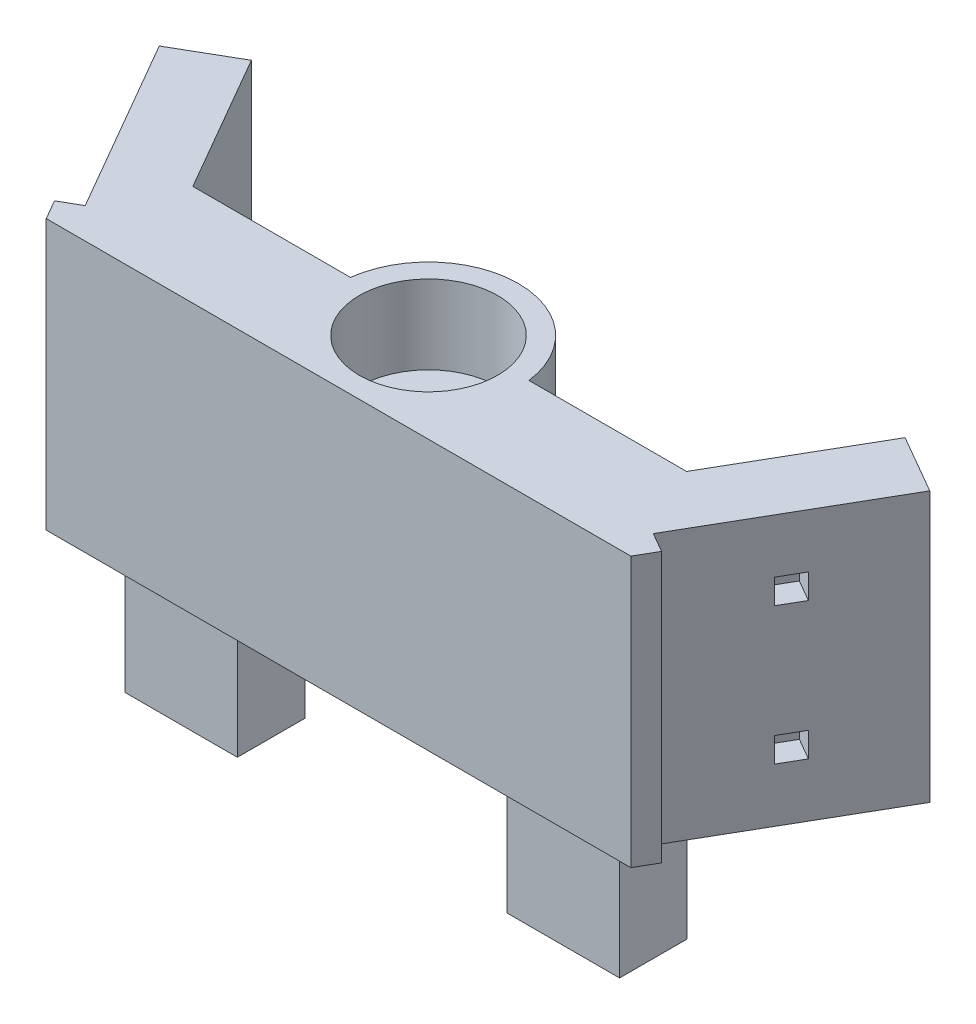
SolidWorks part; units mm, degrees
material "ABS"
ref_plane "Front Plane" through (0, 0, 0) normal (0, 0, 1) x (1, 0, 0)
ref_plane "Top Plane" through (0, 0, 0) normal (0, 1, 0) x (1, 0, 0)
ref_plane "Right Plane" through (0, 0, 0) normal (1, 0, 0) x (0, 0, -1)
sketch "Sketch1" plane through (0, 0, 0) normal (0, 1, 0) x (1, 0, 0)
  line L0 (-13, -4) -> (13, -4)
  line L1 (13, -4) -> (13.5, -3.134)
  line L2 (0, -2.5) -> (13.866, -2.5) construction
  line L3 (0, 0) -> (0, -4) construction
  line L6 (13.5, -3.134) -> (12.634, -2.634)
  line L7 (12.634, -2.634) -> (17.134, 5.1603)
  line L8 (17.134, 5.1603) -> (14.5359, 6.6603)
  line L9 (14.5359, 6.6603) -> (10.9793, 0.5)
  line L10 (-13, -4) -> (-13.5, -3.134)
  line L13 (-13.5, -3.134) -> (-12.634, -2.634)
  line L14 (-12.634, -2.634) -> (-17.134, 5.1603)
  line L15 (-17.134, 5.1603) -> (-14.5359, 6.6603)
  line L16 (-14.5359, 6.6603) -> (-10.9793, 0.5)
  line L17 (-11, 0.5) -> (-11, -2.5) construction
  line L18 (6, 0.5) -> (11, 0.5) construction
  line L19 (6, 0.5) -> (6, -2.5) construction
  line L20 (6, -2.5) -> (11, -2.5) construction
  line L21 (11, 0.5) -> (11, -2.5) construction
  line L22 (3.9686, 0.5) -> (10.9793, 0.5)
  line L23 (-10.9793, 0.5) -> (-3.9686, 0.5)
  line L24 (-6, -2.5) -> (-11, -2.5) construction
  line L25 (-6, 0.5) -> (-6, -2.5) construction
  line L26 (-6, 0.5) -> (-11, 0.5) construction
  circle A0 centre (0, 0) radius 2.5 construction
  arc A1 (-3.9686, 0.5) -> (3.9686, 0.5) centre (0, 0) cw
  dimension "D3" = 5
  dimension "D5" = 1.5
  dimension "D1" = 26
  dimension "D2" = 60
  dimension "D4" = 1.5
  dimension "D6" = 12
  dimension "D7" = 1
  dimension "D8" = 10
  dimension "D9" = 9
  dimension "D10" = 3
  dimension "D11" = 3
  dimension "D12" = 4.5
  dimension "D13" = 5
extrude "Boss-Extrude1" add sketch "Sketch1" along normal blind 12
hole_wizard "Ø2.5 (2.5) Diameter Hole1" positions "Sketch3" profile "Sketch2" hole size "Ø2.5" standard "ISO"
sketch "Sketch3" plane through (0, 12, 0) normal (0, 1, 0) x (1, 0, 0)
  point P0 (0, 0)
sketch "Sketch2" plane through (0, 12, 0) normal (1, 0, 0) x (0, 0, 1)
  line L0 (0, 0) -> (0, 10.7511)
  line L1 (0, 10.7511) -> (1.25, 10)
  line L2 (1.25, 10) -> (1.25, 0)
  line L5 (1.25, 0) -> (0, 0)
  line L10 (0, 10.7511) -> (-1.25, 10) construction
  line L11 (0, -6.35) -> (0, 107.95) construction
  dimension "Hole Dia." = 2.5
  dimension "Hole Depth" = 10
  dimension "Drill Angle" = 118
sketch "Sketch4" plane through (0, 12, 0) normal (0, 1, 0) x (1, 0, 0)
  circle A0 centre (0, 0) radius 3.0762
  dimension "D1" = 6.1524
extrude "Cut-Extrude1" cut sketch "Sketch4" against normal blind 3.5
sketch "Sketch5" plane through (0, 0, 0) normal (0, -1, 0) x (1, 0, 0)
  line L1 (6, 2.5) -> (11, 2.5)
  line L2 (6, 2.5) -> (6, -0.5)
  line L3 (6, -0.5) -> (11, -0.5)
  line L4 (11, 2.5) -> (11, -0.5)
  line L5 (-11, 2.5) -> (-6, 2.5)
  line L6 (-11, 2.5) -> (-11, -0.5)
  line L7 (-11, -0.5) -> (-6, -0.5)
  line L8 (-6, 2.5) -> (-6, -0.5)
extrude "Boss-Extrude2" add sketch "Sketch5" along normal blind 6
sketch "Sketch6" plane through (0, -6, 0) normal (0, -1, 0) x (1, 0, 0)
  line L0 (6, 2.5) -> (6, -0.5) construction
  line L1 (8, 1) -> (-8, 1)
  line L2 (8, 1) -> (8, -1)
  line L3 (8, -1) -> (-8, -1)
  line L4 (-8, 1) -> (-8, -1)
  line L5 (11, 2.5) -> (6, 2.5) construction
  line L6 (8, -1) -> (-8, 1) construction
  dimension "D1" = 2
  dimension "D2" = 1.5
extrude "Cut-Extrude2" [suppressed] cut sketch "Sketch6" against normal blind 14
sketch "Sketch7" plane through (-10.616, 0, 6.1292) normal (-0.866, 0, 0.5) x (0.5, 0, 0.866)
  line L0 (-8.5359, 8.5) -> (-8.5359, 3.5) construction
  line L1 (-9.0859, 9.6) -> (-7.9859, 9.6)
  line L2 (-9.0859, 9.6) -> (-9.0859, 8.5)
  line L3 (-9.0859, 8.5) -> (-7.9859, 8.5)
  line L4 (-7.9859, 9.6) -> (-7.9859, 8.5)
  line L5 (-8.5359, 6) -> (-4.0359, 6) construction
  line L6 (-4.0359, 12) -> (-4.0359, 0) construction
  line L9 (-9.0859, 3.5) -> (-7.9859, 3.5)
  line L10 (-9.0859, 3.5) -> (-9.0859, 2.4)
  line L11 (-9.0859, 2.4) -> (-7.9859, 2.4)
  line L12 (-7.9859, 3.5) -> (-7.9859, 2.4)
  line L14 (-13.0359, 12) -> (-13.0359, 0) construction
  line L15 (-8.5359, 6) -> (-13.0359, 6) construction
  dimension "D1" = 1.1
  dimension "D3" = 5
extrude "Cut-Extrude3" cut sketch "Sketch7" against normal blind 1.1
sketch "Sketch8" plane through (10.616, 0, 6.1292) normal (0.866, 0, 0.5) x (0.5, 0, -0.866)
  line L0 (8.5359, 8.5) -> (8.5359, 3.5) construction
  line L1 (8.5359, 6) -> (13.0359, 6) construction
  line L2 (13.0359, 12) -> (13.0359, 0) construction
  line L3 (8.5359, 6) -> (4.0359, 6) construction
  line L4 (4.0359, 12) -> (4.0359, 0) construction
  line L6 (7.9859, 9.6) -> (9.0859, 9.6)
  line L7 (7.9859, 9.6) -> (7.9859, 8.5)
  line L8 (7.9859, 8.5) -> (9.0859, 8.5)
  line L9 (9.0859, 9.6) -> (9.0859, 8.5)
  line L10 (7.9859, 2.4) -> (9.0859, 2.4)
  line L11 (7.9859, 2.4) -> (7.9859, 3.5)
  line L12 (7.9859, 3.5) -> (9.0859, 3.5)
  line L13 (9.0859, 2.4) -> (9.0859, 3.5)
  dimension "D1" = 1.1
  dimension "D2" = 5
extrude "Cut-Extrude4" cut sketch "Sketch8" against normal blind 1.1
